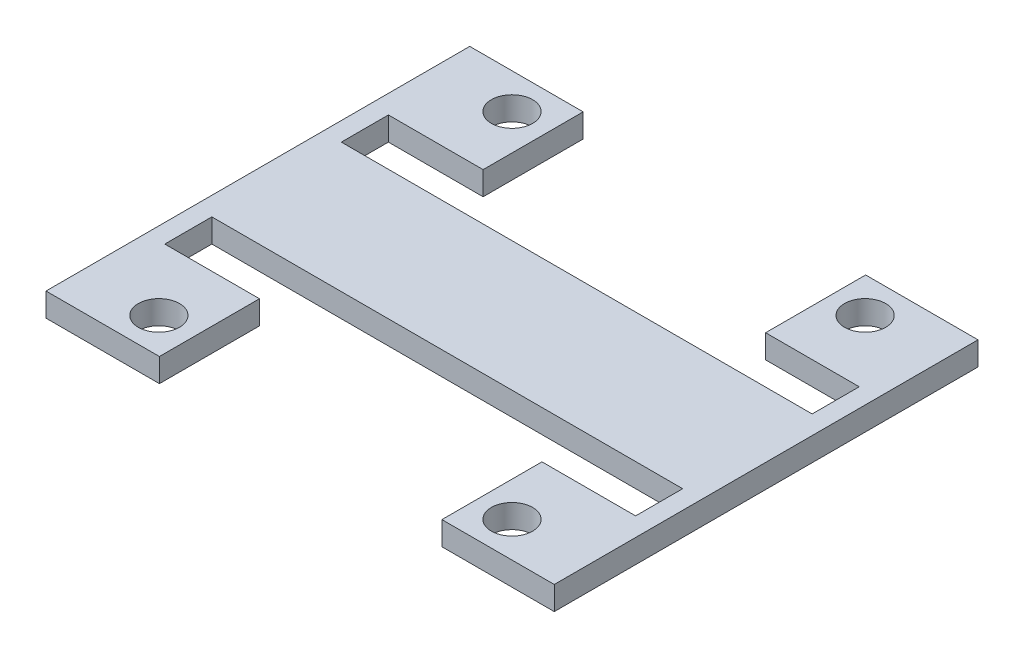
SolidWorks part; units mm, degrees
ref_plane "Front Plane" through (0, 0, 0) normal (0, 0, 1) x (1, 0, 0)
ref_plane "Top Plane" through (0, 0, 0) normal (0, 1, 0) x (1, 0, 0)
ref_plane "Right Plane" through (0, 0, 0) normal (1, 0, 0) x (0, 0, -1)
sketch "Sketch1" plane through (0, 0, 0) normal (0, 1, 0) x (1, 0, 0)
  line L0 (-34.6173, 0) -> (53.1626, 0) construction
  line L7 (-17.9541, -18) -> (-9.9541, -18)
  line L9 (-17.9541, 18) -> (-9.9541, 18)
  line L20 (19.005, -6.25) -> (19.005, -8.75)
  line L24 (10.0459, 18) -> (10.0459, 12.6161)
  line L26 (19.005, -8.75) -> (18.5047, -8.75)
  line L31 (10.0459, 12.6161) -> (-9.9541, 12.6161)
  line L32 (-9.9541, 18) -> (-9.9541, 12.6161)
  line L33 (-21.59, -18) -> (-9.9541, -18)
  line L34 (-21.59, -18) -> (-21.59, 18)
  line L35 (-21.59, 18) -> (-9.9541, 18)
  line L36 (21.59, -18) -> (21.59, 18)
  line L37 (0, 0) -> (0, 6.25)
  line L38 (18.5047, -6.25) -> (19.005, -6.25)
  line L39 (10.0459, -12.6161) -> (-9.9541, -12.6161)
  line L40 (-9.9541, -18) -> (-9.9541, -12.6161)
  line L42 (10.0459, -18) -> (10.0459, -12.6161)
  line L43 (10.0459, -18) -> (21.59, -18)
  line L44 (10.0459, -18) -> (18.0459, -18)
  line L45 (10.0459, 18) -> (18.0459, 18)
  line L46 (10.0459, 18) -> (21.59, 18)
  line L47 (18.5047, -6.25) -> (-18.5, -6.25)
  line L48 (-19.0045, -6.25) -> (-18.5, -6.25)
  line L49 (-19.0045, -8.75) -> (-19.0045, -6.25)
  line L50 (-18.5, 8.75) -> (18.5047, 8.75)
  line L51 (18.5047, 6.25) -> (-18.5, 6.25)
  line L52 (-18.5, -8.75) -> (-19.0045, -8.75)
  line L53 (0.0024, 8.75) -> (-18.5, 8.75)
  line L54 (0.0024, 8.75) -> (18.5047, 8.75)
  line L55 (-18.5, 8.75) -> (-19.0045, 8.75)
  line L56 (-19.0045, 8.75) -> (-19.0045, 6.25)
  line L57 (-19.0045, 6.25) -> (-18.5, 6.25)
  line L58 (18.5047, 6.25) -> (19.005, 6.25)
  line L59 (19.005, 6.25) -> (19.005, 8.75)
  line L60 (19.005, 8.75) -> (18.5047, 8.75)
  line L61 (-18.5, -8.75) -> (18.5047, -8.75)
  circle A0 centre (-15, 15) radius 1.75
  circle A1 centre (15, 15) radius 1.75
  circle A2 centre (15, -15) radius 1.75
  circle A3 centre (-15, -15) radius 1.75
  point P0 (0, 0)
  point P10 (0, 0)
  point P15 (0, 0)
  point P16 (0, 0)
  point P17 (0.0459, 18)
  point P24 (0, 0)
  dimension "D3" = 3.5
  dimension "D4" = 3.5
  dimension "D5" = 3.5
  dimension "D6" = 3.5
  dimension "D11" = 2.5
  dimension "D12" = 38.0095
  dimension "D13" = 18.5024
  dimension "D14" = 38.0095
  dimension "D1" = 30
  dimension "D2" = 30
  dimension "D7" = 36
  dimension "D8" = 36
  dimension "D9" = 43.18
  dimension "D10" = 20
extrude "Boss-Extrude3" add sketch "Sketch1" along normal blind 3
sketch "Sketch3" plane through (0, 3, 0) normal (0, 1, 0) x (1, 0, 0)
  line L0 (0, 0) -> (-16.59, 0)
  line L1 (-21.59, 9.27) -> (21.59, 9.27)
  line L2 (-21.59, 9.27) -> (-21.59, -9.27)
  line L3 (-21.59, -9.27) -> (21.59, -9.27)
  line L4 (21.59, 9.27) -> (21.59, -9.27)
  line L5 (-21.59, 9.27) -> (21.59, -9.27) construction
  line L6 (-21.59, -9.27) -> (21.59, 9.27) construction
  line L7 (-16.59, 0) -> (36.4752, 0)
  line L8 (21.59, 0) -> (21.59, 3.9995)
  line L9 (21.59, 3.9995) -> (21.59, -3.9981)
  line L10 (21.59, -3.9981) -> (12.59, -3.9981)
  line L11 (12.59, -3.9981) -> (12.59, 3.9995)
  line L12 (12.59, 3.9995) -> (21.59, 3.9995)
  line L13 (-21.59, 0) -> (-21.59, 3.75)
  line L14 (-21.59, 3.75) -> (-21.59, -3.75)
  line L15 (-21.59, -3.75) -> (-16.59, -3.75)
  line L16 (-16.59, -3.75) -> (-16.59, 3.75)
  line L17 (-16.59, 3.75) -> (-21.59, 3.75)
  line L18 (12.59, 0.0007) -> (-3.408, 0)
  line L19 (-16.59, 0) -> (-4.576, 0)
  line L20 (21.59, 0) -> (-1.9118, 0)
  line L21 (-1.9118, 0) -> (-3.9118, 0)
  line L22 (-3.9118, 0) -> (-3.9118, 2)
  line L23 (-3.9118, 2) -> (-1.9118, 2)
  line L24 (-1.9118, 2) -> (-1.9118, -2)
  line L25 (-1.9118, -2) -> (-3.9118, -2)
  line L26 (-3.9118, -2) -> (-3.9118, -0.0848)
  line L27 (-3.9118, -0.0848) -> (-3.9118, 0)
  line L28 (21.59, -18) -> (21.59, 18) construction
  point P0 (0, 0)
  dimension "D1" = 43.18
  dimension "D2" = 18.54
  dimension "D3" = 3.75
  dimension "D4" = 3.75
  dimension "D5" = 5
  dimension "D6" = 23.5018
  dimension "D7" = 2
  dimension "D8" = 2
  dimension "D9" = 2
  dimension "D10" = 12.6782
sketch "Sketch4" plane through (0, 3, 0) normal (0, 1, 0) x (1, 0, 0)
  line L0 (-21.59, -9.27) -> (-21.59, -18)
  line L4 (-21.59, -9.27) -> (-21.59, 9.27)
  line L5 (19.005, -8.9) -> (19.255, -8.9)
  line L6 (21.59, 9.27) -> (19.255, 8.2674) construction
  line L7 (-17.4676, -7.5) -> (-22.2811, -7.5) construction
  line L8 (19.255, 6.1) -> (19.255, 8.8828)
  line L9 (-22.2811, -7.5) -> (-22.2811, 7.5) construction
  line L10 (-22.2811, 7.5) -> (-19.2545, 7.5) construction
  line L11 (-21.59, -18) -> (-9.9541, -18)
  line L12 (-9.9541, -18) -> (-9.9541, -12.6161)
  line L13 (-9.9541, -12.6161) -> (10.0459, -12.6161)
  line L14 (10.0459, -12.6161) -> (10.0459, -18)
  line L15 (10.0459, -18) -> (21.59, -18)
  line L18 (-21.59, 9.27) -> (-21.59, 18)
  line L19 (-21.59, 18) -> (-9.9541, 18)
  line L20 (-9.9541, 18) -> (-9.9541, 12.6161)
  line L21 (-9.9541, 12.6161) -> (10.0459, 12.6161)
  line L22 (10.0459, 12.6161) -> (10.0459, 18)
  line L23 (10.0459, 18) -> (21.59, 18)
  line L26 (19.957, 7.5) -> (19.957, -7.5) construction
  line L27 (19.957, -7.5) -> (19.255, -7.5) construction
  line L28 (19.005, 6.1) -> (19.255, 6.1)
  line L29 (19.005, -8.9) -> (-19.0045, -8.9)
  line L30 (-19.2545, -8.2672) -> (-21.59, -9.27) construction
  line L31 (-25.3402, 0) -> (40.0114, 0) construction
  line L32 (19.255, 7.5) -> (19.957, 7.5) construction
  line L33 (19.005, -6.1) -> (-19.0045, -6.1)
  line L35 (-19.0045, -8.9) -> (19.005, -8.9)
  line L37 (-19.0045, -6.1) -> (19.005, -6.1)
  line L39 (-19.0045, 6.1) -> (19.005, 6.1)
  line L41 (-19.0045, 8.9) -> (19.005, 8.9)
  line L43 (19.255, -8.9) -> (19.255, -6.1)
  line L44 (19.255, -6.1) -> (19.005, -6.1)
  line L45 (-19.0045, -6.1) -> (-19.2545, -6.1)
  line L46 (-19.2545, -6.1) -> (-19.2545, -8.9)
  line L47 (-19.2545, -8.9) -> (-19.0045, -8.9)
  line L48 (19.255, 8.9) -> (19.005, 8.9)
  line L49 (-19.0045, 6.1) -> (-19.2545, 6.1)
  line L50 (14.207, 6.1) -> (-17.4676, -7.5) construction
  line L51 (-19.2545, 8.9) -> (-19.0045, 8.9)
  line L52 (-19.2545, 6.1) -> (-19.2545, 8.9)
  line L54 (19.255, -8.9) -> (-19.2545, -8.9)
  line L55 (19.255, -8.9) -> (19.255, -6.1)
  line L56 (19.255, -6.1) -> (-19.2545, -6.1)
  line L57 (-19.2545, -8.9) -> (-19.2545, -6.1)
  line L58 (-19.2545, 6.1) -> (19.255, 6.1)
  line L59 (-19.2545, 6.1) -> (-19.2545, 8.9)
  line L60 (-19.2545, 8.9) -> (19.255, 8.9)
  line L61 (19.255, 6.1) -> (19.255, 8.9)
  circle A1 centre (15, -15) radius 1.75
  circle A2 centre (-15, -15) radius 1.75
  circle A3 centre (-15, 15) radius 1.75
  circle A4 centre (15, 15) radius 1.7781
  point P0 (0, 0)
  line M27 (19.005, -8.75) -> (-19.0045, -8.75)
  line M28 (-19.0045, -8.75) -> (-19.0045, -6.25)
  line M29 (-19.0045, -6.25) -> (19.005, -6.25)
  line M30 (19.005, -6.25) -> (19.005, -8.75)
  line M31 (19.005, 8.75) -> (19.005, 6.25)
  line M32 (19.005, 6.25) -> (-19.0045, 6.25)
  line M33 (-19.0045, 6.25) -> (-19.0045, 8.75)
  line M34 (-19.0045, 8.75) -> (19.005, 8.75)
  dimension "D1" = 18.54
  dimension "D2" = 43.18
  dimension "D3" = 0.25
  dimension "D4" = 0.25
  dimension "D5" = 38.0095
  dimension "D6" = 0.25
  dimension "D7" = 0.25
sketch "Sketch5" plane through (21.59, 0, 0) normal (1, 0, 0) x (0, 0, -1)
  line L0 (0, -5.6906) -> (0, 9.6238) construction
  line L1 (18, -1) -> (11.53, -1)
  line L2 (-18, 3) -> (-11.53, 3)
  line L3 (-18, 3) -> (-18, -1)
  line L4 (-18, -1) -> (-11.53, -1)
  line L5 (-11.53, 3) -> (-11.53, -1)
  line L6 (11.53, 3) -> (11.53, -1)
  line L7 (18, 3) -> (11.53, 3)
  line L8 (18, 3) -> (18, -1)
  dimension "D1" = 4
  dimension "D2" = 6.47
extrude "Cut-Extrude7" cut sketch "Sketch4" against normal through all contours M31 M34 M33 M32 | L8 L61 L48 L41 L51 L52 L49 L39 L28 M34 M31 M32 M33 | L46 L47 L29 L5 L43 L44 L33 L45 M30 M27 M28 M29
sketch "Sketch7" plane through (21.59, 0, 0) normal (1, 0, 0) x (0, 0, -1)
  line L0 (-18, 0) -> (-18, 1)
  line L5 (-18, 3) -> (-18, -1) construction
  line L7 (18, 0) -> (-18, 0)
  line L8 (18, 0) -> (18, 1)
  line L9 (18, 1) -> (-18, 1)
  line L10 (-18, 0) -> (-18, 1)
  line M6 (-18, 0) -> (18, 0)
  line M7 (18, 0) -> (18, 3)
  line M9 (-18, 3) -> (-18, 0)
  dimension "D1" = 1
extrude "Cut-Extrude8" cut sketch "Sketch7" against normal through all contours L9 M7 M9 M6
sketch "Sketch9" plane through (0, 3, 0) normal (0, 1, 0) x (1, 0, 0)
  line L0 (-26.5021, 0) -> (31.2458, 0) construction
  line L3 (-19.2545, -6.1) -> (-19.2545, -8.9)
  line L4 (-19.2545, -8.9) -> (19.255, -8.9)
  line L5 (19.255, -8.9) -> (19.255, -6.1)
  line L6 (19.255, -6.1) -> (-19.2545, -6.1)
  line L7 (19.255, -8.9) -> (-19.2545, -6.1)
  line L8 (-19.2545, -8.9) -> (19.255, -6.1)
  line L10 (-18.9908, -9.45) -> (18.9912, -9.45)
  line L11 (-18.9908, -9.45) -> (-18.9908, -5.55)
  line L12 (-18.9908, -5.55) -> (18.9912, -5.55)
  line L13 (18.9912, -9.45) -> (18.9912, -5.55)
  line L14 (-18.9908, -9.45) -> (18.9912, -5.55) construction
  line L15 (-18.9908, -5.55) -> (18.9912, -9.45) construction
  line L19 (19.9912, 5.5492) -> (19.9912, 9.4508)
  line L20 (-19.9908, -5.5492) -> (19.9912, -5.5492)
  line L21 (-19.9908, -5.5492) -> (-19.9908, -9.4508)
  line L22 (-19.9908, -9.4508) -> (19.9912, -9.4508)
  line L23 (19.9912, -5.5492) -> (19.9912, -9.4508)
  line L24 (-19.9908, -5.5492) -> (19.9912, -9.4508) construction
  line L25 (-19.9908, -9.4508) -> (19.9912, -5.5492) construction
  line L26 (-19.9908, -9.4508) -> (19.9912, -9.4508)
  line L27 (-19.9908, -9.4508) -> (-19.9908, -5.5492)
  line L28 (-19.9908, -5.5492) -> (19.9912, -5.5492)
  line L29 (19.9912, -9.4508) -> (19.9912, -5.5492)
  line L30 (-19.9908, 5.5492) -> (19.9912, 5.5492)
  line L31 (-19.9908, 9.4508) -> (19.9912, 9.4508)
  line L32 (-19.9908, 5.5492) -> (-19.9908, 9.4508)
  point P5 (0.0002, -7.5)
  point P20 (0.0002, -7.5)
  line M9 (19.255, 8.9) -> (19.255, 6.1)
  line M10 (19.255, 6.1) -> (-19.2545, 6.1)
  line M11 (-19.2545, 6.1) -> (-19.2545, 8.9)
  line M12 (-19.2545, 8.9) -> (19.255, 8.9)
  line M13 (-19.2545, -8.9) -> (-19.2545, -6.1)
  line M14 (-19.2545, -6.1) -> (19.255, -6.1)
  line M15 (19.255, -6.1) -> (19.255, -8.9)
  line M16 (19.255, -8.9) -> (-19.2545, -8.9)
  dimension "D1" = 3.9
  dimension "D2" = 1
  dimension "D3" = 1
extrude "Cut-Extrude9" cut sketch "Sketch9" against normal blind 10 contours L10 L13 L4 L11 | L32 L30 L19 L31 M12 M9 M10 M11 | L6 L13 L12 L11 | L23 L20 L21 L22 L13 L10 L11 L4 L12 M13 M14 M15 M16
sketch "Sketch10" plane through (0, 3, 0) normal (0, 1, 0) x (1, 0, 0)
  line L1 (-19.9908, -5.5492) -> (-19.9908, -9.4508)
  line L3 (19.9912, -5.5492) -> (19.9912, -9.4508)
  line L4 (0, 0) -> (29.449, 0) construction
  line L5 (-19.9998, -5.5) -> (20.0002, -5.5)
  line L6 (-19.9998, -5.5) -> (-19.9998, -9.5)
  line L7 (-19.9998, -9.5) -> (20.0002, -9.5)
  line L8 (20.0002, -5.5) -> (20.0002, -9.5)
  line L9 (-19.9998, -5.5) -> (20.0002, -9.5) construction
  line L10 (-19.9998, -9.5) -> (20.0002, -5.5) construction
  line L11 (29.449, 0) -> (-32.5926, 0) construction
  line L13 (-19.9908, 9.4508) -> (-19.9908, 5.5492)
  line L16 (-19.9998, 5.5) -> (20.0002, 5.5)
  line L17 (-19.9998, 5.5) -> (-19.9998, 9.5)
  line L18 (-19.9998, 9.5) -> (20.0002, 9.5)
  line L19 (20.0002, 5.5) -> (20.0002, 9.5)
  line L20 (-19.9998, 5.5) -> (20.0002, 9.5) construction
  line L21 (-19.9998, 9.5) -> (20.0002, 5.5) construction
  point P4 (0.0002, -7.5)
  point P20 (0.0002, 7.5)
  line M7 (-19.9908, -5.5492) -> (19.9912, -5.5492)
  line M8 (19.9912, -5.5492) -> (19.9912, -9.4508)
  line M9 (19.9912, -9.4508) -> (-19.9908, -9.4508)
  line M10 (-19.9908, -9.4508) -> (-19.9908, -5.5492)
  line M27 (19.9912, 5.5492) -> (-19.9908, 5.5492)
  line M28 (-19.9908, 5.5492) -> (-19.9908, 9.4508)
  line M29 (-19.9908, 9.4508) -> (19.9912, 9.4508)
  line M30 (19.9912, 9.4508) -> (19.9912, 5.5492)
  dimension "D1" = 4
  dimension "D2" = 40
  dimension "D3" = 4
  dimension "D4" = 40
extrude "Cut-Extrude11" cut sketch "Sketch10" against normal through all contours M27 M30 M29 M28 | L8 L5 L6 L7 M10 M7 M8 M9 | L16 L19 L18 L17 M30 M27 M28 M29
sketch "Sketch11" plane through (0, 3, 0) normal (0, 1, 0) x (1, 0, 0)
  line L0 (-9.9541, 18) -> (-9.9541, 12.6161) construction
  line L1 (10.0459, -12.6161) -> (-9.9541, -12.6161)
  line L2 (10.0459, -12.6161) -> (10.0459, 12.6161)
  line L3 (10.0459, 12.6161) -> (-9.9541, 12.6161)
  line L4 (-9.9541, -12.6161) -> (-9.9541, 12.6161)
  line L5 (10.0459, 12.6161) -> (-9.9541, 12.6161) construction
  line L6 (10.0459, -9.5) -> (-9.9541, -9.5)
  line L7 (-19.9998, -9.5) -> (20.0002, -9.5) construction
  line L8 (-9.9541, 9.4749) -> (10.0459, 9.5)
  line L9 (-19.9998, 9.5) -> (20.0002, 9.5) construction
  line M12 (10.0459, 12.6161) -> (-9.9541, 12.6161)
  line M18 (-9.9541, -12.6161) -> (10.0459, -12.6161)
  line M23 (-19.9998, 9.5) -> (20.0002, 9.5)
  line M27 (20.0002, -9.5) -> (-19.9998, -9.5)
extrude "Cut-Extrude12" cut sketch "Sketch11" against normal blind 10 contours L4 L2 M18 M27 | L4 L2 M23 M12
sketch "Sketch12" plane through (0, 3, 0) normal (0, 1, 0) x (1, 0, 0)
  line L0 (-9.9541, -18) -> (-11.9541, -18)
  line L1 (-21.59, -18) -> (-9.9541, -18) construction
  line L2 (-11.9541, -18) -> (-11.9541, 18)
  line L3 (-21.59, 18) -> (-9.9541, 18) construction
  line L4 (-11.9541, 18) -> (-9.9541, 18)
  line L5 (-9.9541, 18) -> (-9.9541, -18)
  line L6 (10.0459, -18) -> (12.0459, -18)
  line L7 (10.0459, -18) -> (21.59, -18) construction
  line L8 (12.0459, -18) -> (12.0459, 18)
  line L9 (10.0459, 18) -> (21.59, 18) construction
  line L10 (12.0459, 18) -> (10.0459, 18)
  line L11 (10.0459, 18) -> (10.0459, -18)
  line L12 (10.0459, 9.5) -> (20.0002, 9.5) construction
  line L13 (-11.9541, -18) -> (-9.9541, -18)
  line L14 (-11.9541, -18) -> (-11.9541, -9.5)
  line L15 (-11.9541, -9.5) -> (-9.9541, -9.5)
  line L16 (-9.9541, -18) -> (-9.9541, -9.5)
  line L17 (10.0459, -18) -> (12.0459, -18)
  line L18 (10.0459, -18) -> (10.0459, -9.6559)
  line L20 (12.0459, -18) -> (12.0459, -9.6559)
  line L21 (10.0459, 18) -> (12.0459, 18)
  line L22 (10.0459, 18) -> (10.0459, 9.5)
  line L23 (10.0459, 9.5) -> (12.0459, 9.5)
  line L24 (12.0459, 18) -> (12.0459, 9.5)
  line L26 (-11.9541, 18) -> (-9.9541, 18)
  line L27 (-11.9541, 18) -> (-11.9541, 9.5)
  line L28 (-11.9541, 9.5) -> (-9.9541, 9.5)
  line L29 (-9.9541, 18) -> (-9.9541, 9.5)
  line L30 (10.0459, -9.5) -> (12.0459, -9.5)
  line L31 (10.0459, -9.5) -> (10.0459, -18)
  line L32 (10.0459, -18) -> (12.0459, -18)
  line L33 (12.0459, -9.5) -> (12.0459, -18)
  line M10 (-9.9541, -18) -> (-9.9541, -9.5)
  line M11 (-9.9541, -9.5) -> (-19.9998, -9.5)
  line M15 (20.0002, -9.5) -> (10.0459, -9.5)
  line M16 (10.0459, -9.5) -> (10.0459, -18)
  line M17 (10.0459, -18) -> (21.59, -18)
  line M19 (21.59, 18) -> (10.0459, 18)
  line M20 (10.0459, 18) -> (10.0459, 9.5)
  line M21 (10.0459, 9.5) -> (20.0002, 9.5)
  line M25 (-19.9998, 9.5) -> (-9.9541, 9.5)
  line M26 (-9.9541, 9.5) -> (-9.9541, 18)
  line M27 (-9.9541, 18) -> (-21.59, 18)
  line M29 (-21.59, -18) -> (-9.9541, -18)
  dimension "D1" = 2
  dimension "D2" = 2
extrude "Cut-Extrude15" cut sketch "Sketch12" against normal blind 10 contours L2 M29 M10 M11 | L2 M25 M26 M27 | L8 M21 M19 M20 | L8 L11 M17 M15 M16
